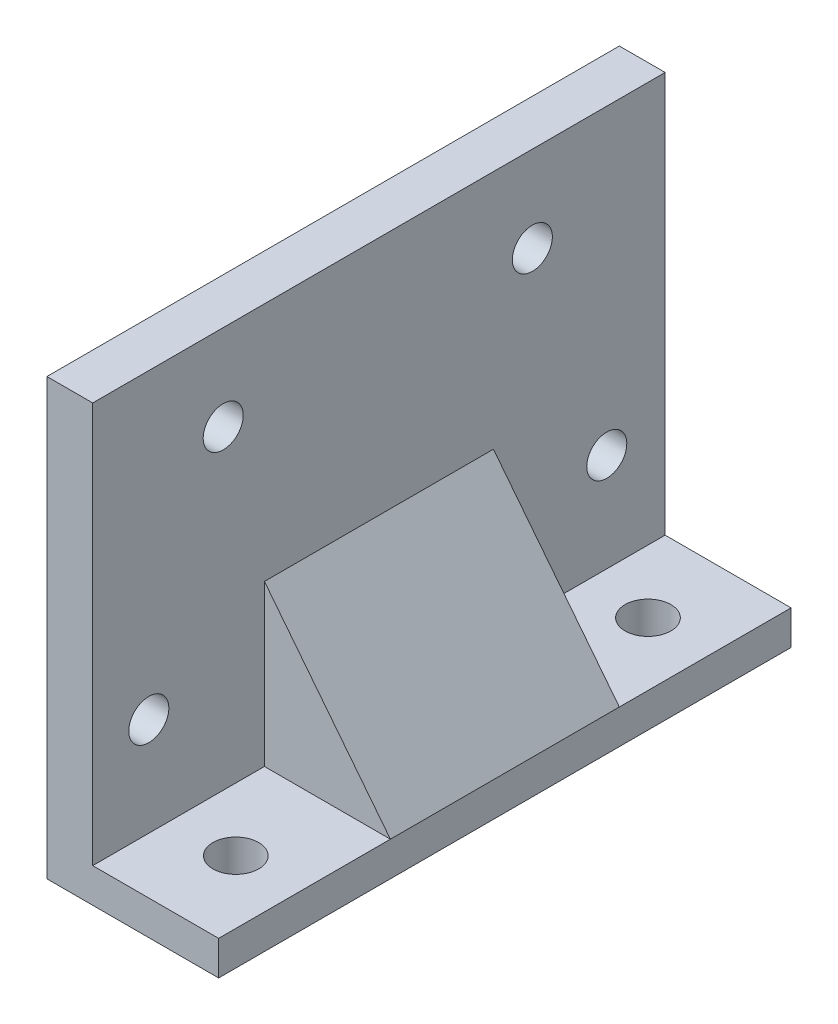
SolidWorks part; units mm, degrees
ref_plane "Front Plane" through (0, 0, 0) normal (0, 0, 1) x (1, 0, 0)
ref_plane "Top Plane" through (0, 0, 0) normal (0, 1, 0) x (1, 0, 0)
ref_plane "Right Plane" through (0, 0, 0) normal (1, 0, 0) x (0, 0, -1)
sketch "Sketch1" plane through (0, 0, 0) normal (0, 0, 1) x (1, 0, 0)
  line L0 (0, 38) -> (0, 0)
  line L1 (0, 0) -> (15, 0)
  line L2 (15, 0) -> (15, 3)
  line L3 (15, 3) -> (4, 3)
  line L4 (4, 3) -> (4, 38)
  line L5 (4, 38) -> (0, 38)
  dimension "D1" = 35
  dimension "D2" = 3
  dimension "D3" = 4
  dimension "D4" = 15
extrude "Boss-Extrude1" add sketch "Sketch1" along normal blind 50
sketch "Sketch2" plane through (0, 3, 0) normal (0, 1, 0) x (1, 0, 0)
  line L6 (15, -25) -> (4, -25) construction
  line L12 (15, -50) -> (15, 0) construction
  line L13 (4, -50) -> (4, 0) construction
  line L14 (4, -35) -> (4, -15)
  line L15 (4, -50) -> (4, 0) construction
  line L16 (4, -15) -> (15, -15)
  line L17 (15, -15) -> (15, -35)
  line L18 (15, -35) -> (4, -35)
  dimension "D1" = 10
  dimension "D2" = 10
extrude "Boss-Extrude2" add sketch "Sketch2" along normal blind 30
sketch "Sketch3" plane through (0, 0, 50) normal (0, 0, 1) x (1, 0, 0)
  line L4 (4, 3) -> (4, 38) construction
  line L8 (4, 33) -> (15, 33) construction
  line L10 (4, 33) -> (4, 17)
  line L13 (4, 17) -> (15, 3)
  line L14 (4, 33) -> (15, 33)
  line L15 (15, 33) -> (15, 3)
  dimension "D1" = 16
extrude "Cut-Extrude1" cut sketch "Sketch3" against normal through all
sketch "Sketch4" plane through (0, 0, 0) normal (-1, 0, 0) x (0, 0, 1)
  line L0 (25, 38) -> (25, 0) construction
  line L2 (50, 38) -> (0, 38) construction
  line L3 (50, 0) -> (0, 0) construction
  line L4 (50, 38) -> (50, 0) construction
  line L5 (50, 38) -> (0, 38) construction
  circle A12 centre (5.1, 11.6) radius 1.75
  circle A13 centre (11.6, 30.5) radius 1.75
  circle A16 centre (45.1, 11.6) radius 1.75
  circle A17 centre (38.6, 30.5) radius 1.75
  dimension "D1" = 11.6
  dimension "D4" = 40
  dimension "D22" = 3.5
  dimension "D5" = 7.5
  dimension "D8" = 7.5
  dimension "D3" = 27
  dimension "D6" = 4.9
  dimension "D7" = 13.4
extrude "Cut-Extrude2" cut sketch "Sketch4" against normal blind 30
sketch "Sketch5" plane through (0, 3, 0) normal (0, 1, 0) x (1, 0, 0)
  line L0 (0, -25) -> (15, -25) construction
  line L4 (15, -50) -> (15, 0) construction
  line L5 (0, -50) -> (15, -50) construction
  line L6 (0, -50) -> (0, 0) construction
  circle A2 centre (9.5, -43) radius 2
  circle A3 centre (9.5, -7) radius 2
  dimension "D1" = 5.5
  dimension "D2" = 7
extrude "Cut-Extrude3" cut sketch "Sketch5" against normal blind 30
sketch "Sketch6" plane through (0, 0, 0) normal (-1, 0, 0) x (0, 0, 1)
  line L0 (50, 0) -> (0, 0) construction
  line L1 (28.85, 14) -> (39.85, 14)
  line L2 (28.85, 14) -> (28.85, 8.5)
  line L3 (28.85, 8.5) -> (39.85, 8.5)
  line L4 (39.85, 14) -> (39.85, 8.5)
  circle A0 centre (45.1, 11.6) radius 1.75 construction
  dimension "D1" = 5.25
  dimension "D2" = 11
  dimension "D3" = 5.5
  dimension "D4" = 14
extrude "Cut-Extrude4" cut sketch "Sketch6" against normal blind 2
